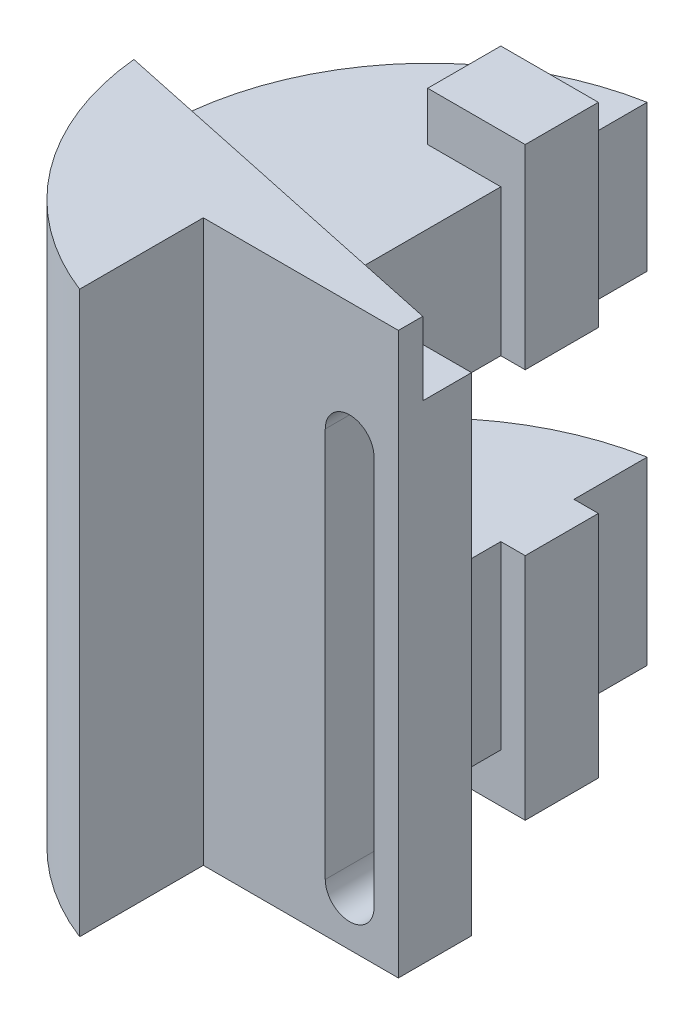
SolidWorks part; units mm, degrees
material "AISI 1020"
ref_plane "Front Plane" through (0, 0, 0) normal (0, 0, 1) x (1, 0, 0)
ref_plane "Top Plane" through (0, 0, 0) normal (0, 1, 0) x (1, 0, 0)
ref_plane "Right Plane" through (0, 0, 0) normal (1, 0, 0) x (0, 0, -1)
sketch "Sketch1" plane through (0, 0, 0) normal (0, 1, 0) x (1, 0, 0)
  line L0 (0, 0) -> (0, 25.3628)
  line L1 (0, 25.3628) -> (40, 25.3628)
  line L2 (40, 25.3628) -> (40, 40.3628)
  line L3 (40, 40.3628) -> (10, 40.3628)
  line L4 (10, 40.3628) -> (10, 106.3628)
  arc A0 (10, 106.3628) -> (0, 0) centre (20, 51.7711) ccw
  dimension "D6" = 55.5
  dimension "D1" = 40
  dimension "D2" = 15
  dimension "D3" = 10
  dimension "D4" = 30
  dimension "D5" = 66
extrude "Boss-Extrude1" add sketch "Sketch1" along normal blind 115
sketch "Sketch2" plane through (0, 115, 0) normal (0, 1, 0) x (1, 0, 0)
  line L0 (40, 30.3628) -> (-35.235, 46.3545)
  line L1 (40, 25.3628) -> (40, 40.3628) construction
  line L7 (0, 0) -> (0, 25.3628)
  line L8 (0, 25.3628) -> (40, 25.3628)
  line L9 (40, 25.3628) -> (40, 40.3628)
  line L10 (40, 40.3628) -> (10, 40.3628)
  line L11 (10, 40.3628) -> (10, 106.3628)
  line L14 (40, 30.3628) -> (40, 40.3628)
  line L15 (40, 40.3628) -> (10, 40.3628)
  line L16 (10, 40.3628) -> (10, 106.3628)
  arc A0 (10, 106.3628) -> (0, 0) centre (20, 51.7711) ccw construction
  arc A2 (10, 106.3628) -> (0, 0) centre (20, 51.7711) ccw
  arc A3 (10, 106.3628) -> (-35.235, 46.3545) centre (20, 51.7711) ccw
  dimension "D1" = 5
  dimension "D2" = 78
  dimension "D3" = 0
extrude "Cut-Extrude1" cut sketch "Sketch2" against normal blind 15
sketch "Sketch3" plane through (0, 100, 0) normal (0, 1, 0) x (1, 0, 0)
  line L0 (10, 40.3628) -> (10, 106.3628) construction
  line L1 (-5, 91.3628) -> (15, 91.3628)
  line L2 (-5, 91.3628) -> (-5, 76.3628)
  line L3 (-5, 76.3628) -> (15, 76.3628)
  line L4 (15, 91.3628) -> (15, 76.3628)
  dimension "D1" = 20
  dimension "D2" = 15
  dimension "D3" = 15
  dimension "D4" = 5
extrude "Boss-Extrude2" add sketch "Sketch3" against normal offset from surface (120 mm away) 10 from offset 10
sketch "Sketch5" plane through (15, 0, 0) normal (1, 0, 0) x (0, 0, -1)
  line L0 (106.3628, 100) -> (106.3628, 0) construction
  line L1 (106.3628, 70) -> (66.3628, 70)
  line L2 (106.3628, 70) -> (106.3628, 37)
  line L3 (106.3628, 37) -> (66.3628, 37)
  line L4 (66.3628, 70) -> (66.3628, 37)
  dimension "D1" = 30
  dimension "D2" = 33
  dimension "D3" = 40
extrude "Cut-Extrude2" cut sketch "Sketch5" against normal through all
sketch "Sketch6" plane through (0, 0, -40.3628) normal (0, 0, -1) x (-1, 0, 0)
  line L0 (-30, 90) -> (-30, 10) construction
  line L1 (-25, 90) -> (-25, 10)
  line L2 (-35, 90) -> (-35, 10)
  line L4 (-40, 100) -> (-40, 0) construction
  line L5 (-40, 0) -> (-10, 0) construction
  arc A0 (-25, 90) -> (-35, 90) centre (-30, 90) ccw
  arc A1 (-35, 10) -> (-25, 10) centre (-30, 10) ccw
  point P2 (-30, 50)
  dimension "D2" = 5
  dimension "D1" = 10
  dimension "D3" = 80
  dimension "D4" = 10
extrude "Cut-Extrude3" cut sketch "Sketch6" against normal through all
equation "\"a\" = 55.5"
equation "\"b\" = 66"
equation "\"c\"= 33"
